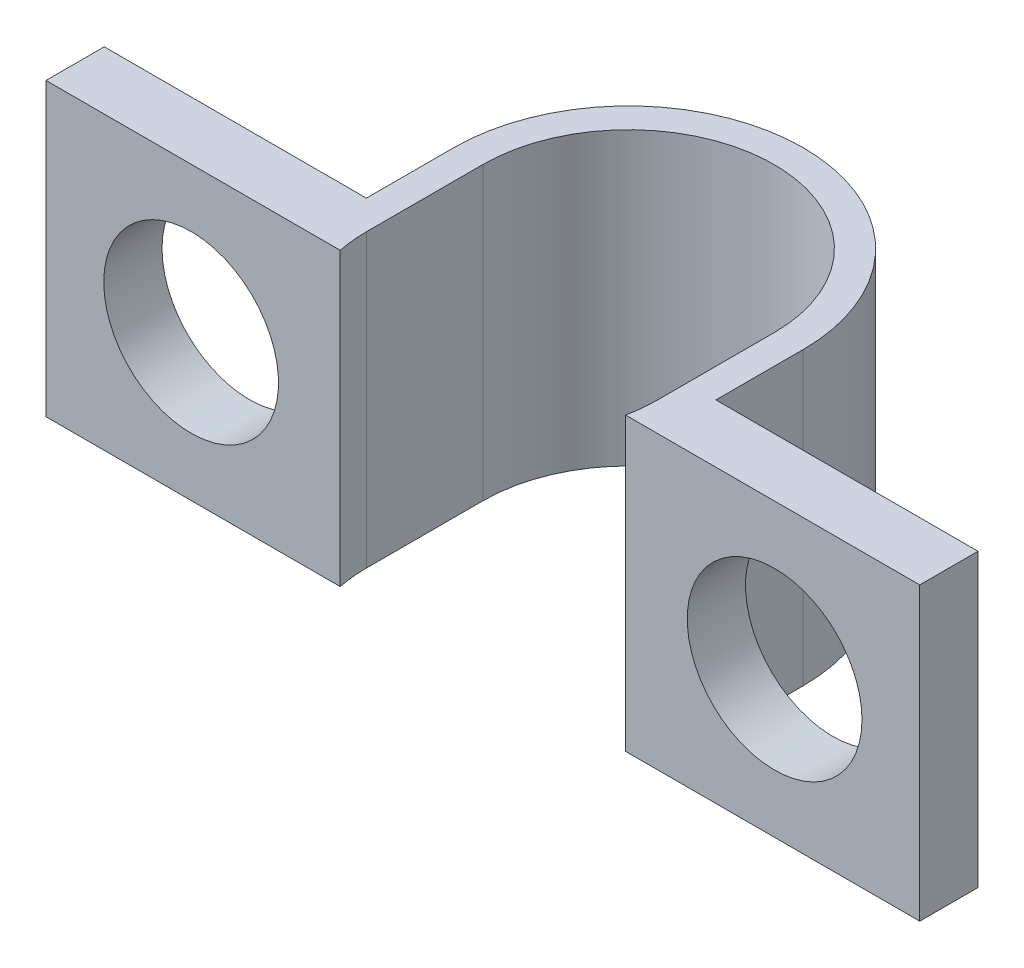
SolidWorks part; units mm, degrees
ref_plane "Front Plane" through (0, 0, 0) normal (0, 0, 1) x (1, 0, 0)
ref_plane "Top Plane" through (0, 0, 0) normal (0, 1, 0) x (1, 0, 0)
ref_plane "Right Plane" through (0, 0, 0) normal (1, 0, 0) x (0, 0, -1)
sketch "Sketch1" plane through (0, 0, 0) normal (0, 1, 0) x (1, 0, 0)
  line L0 (-3, 0.5) -> (-3, 2)
  line L1 (-7.5, 0.5) -> (-3, 0.5)
  line L2 (-7.5, 0.5) -> (-7.5, -0.5)
  line L3 (-7.5, -0.5) -> (-2.4495, -0.5)
  line L4 (7.5, 0.5) -> (7.5, -0.5)
  line L5 (-7.5, 0.5) -> (-2.5, 0.1667) construction
  line L6 (-7.5, -0.5) -> (-2.4945, -0.1663) construction
  line L8 (3, 0.5) -> (3, 2)
  line L9 (-2.5, 0) -> (-2.5, 2)
  line L10 (2.5, 0) -> (2.5, 2)
  line L12 (2.4495, -0.5) -> (7.5, -0.5)
  line L13 (2.5, 0.1667) -> (7.5, 0.5) construction
  line L14 (2.4945, -0.1663) -> (7.5, -0.5) construction
  line L15 (3, 0.5) -> (7.5, 0.5)
  line L16 (-3, 0) -> (-3, 2) construction
  line L17 (3, 0) -> (3, 2) construction
  arc A5 (3, 2) -> (-3, 2) centre (0, 2) ccw
  arc A6 (2.5, 2) -> (-2.5, 2) centre (0, 2) ccw
  arc A7 (-2.5, 0) -> (-2.4495, -0.5) centre (0, 0) ccw
  arc A10 (-3, 0) -> (3, 0) centre (0, 0) ccw construction
  arc A11 (2.4495, -0.5) -> (2.5, 0) centre (0, 0) ccw
  arc A12 (-2.5, 0) -> (2.5, 0) centre (0, 0) ccw construction
  point P0 (0, 0)
  point P9 (0, 1)
  dimension "D1" = 15
  dimension "D3" = 3
  dimension "D2" = 1
  dimension "D5" = 0.5
extrude "Boss-Extrude1" add sketch "Sketch1" along normal blind 5
sketch "Sketch2" plane through (0, 0, -0.5) normal (0, 0, -1) x (-1, 0, 0)
  line L0 (0, 3.2221) -> (0, -4.8636) construction
  line L1 (7.5, 5) -> (7.5, 0) construction
  circle A0 centre (5.0084, 2.5) radius 1.5
  circle A1 centre (-5.0084, 2.5) radius 1.5
  point P8 (7.5, 2.5)
  dimension "D2" = 3
extrude "Cut-Extrude1" cut sketch "Sketch2" against normal through all
